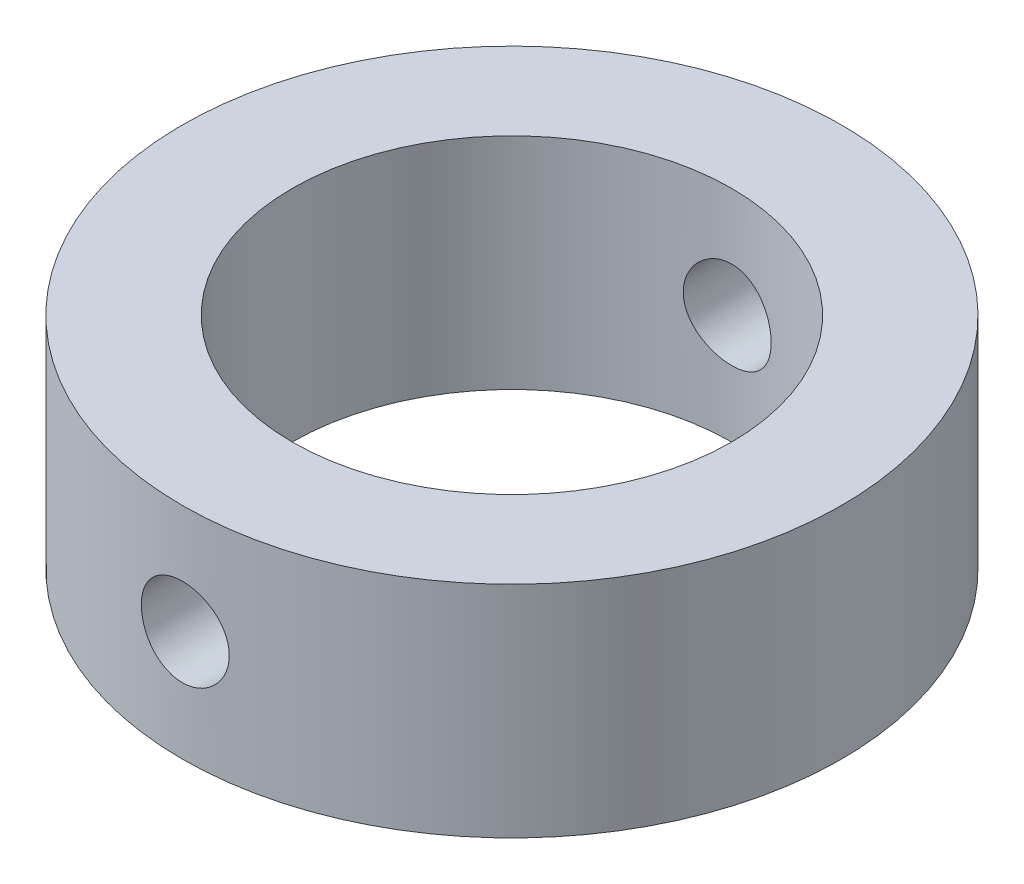
SolidWorks part; units mm, degrees
ref_plane "Front Plane" through (0, 0, 0) normal (0, 0, 1) x (1, 0, 0)
ref_plane "Top Plane" through (0, 0, 0) normal (0, 1, 0) x (1, 0, 0)
ref_plane "Right Plane" through (0, 0, 0) normal (1, 0, 0) x (0, 0, -1)
sketch "Croquis1" plane through (0, 0, 0) normal (0, 1, 0) x (1, 0, 0)
  circle A0 centre (0, 0) radius 22.5
  circle A1 centre (0, 0) radius 15
  dimension "D1" = 45
  dimension "D2" = 30
extrude "Saliente-Extruir1" add sketch "Croquis1" along normal blind 15
sketch "Croquis2" plane through (0, 0, 0) normal (0, 0, 1) x (1, 0, 0)
  circle A0 centre (0, 7.5239) radius 3
  dimension "D1" = 6
extrude "Cortar-Extruir1" cut sketch "Croquis2" against normal mid plane 85
